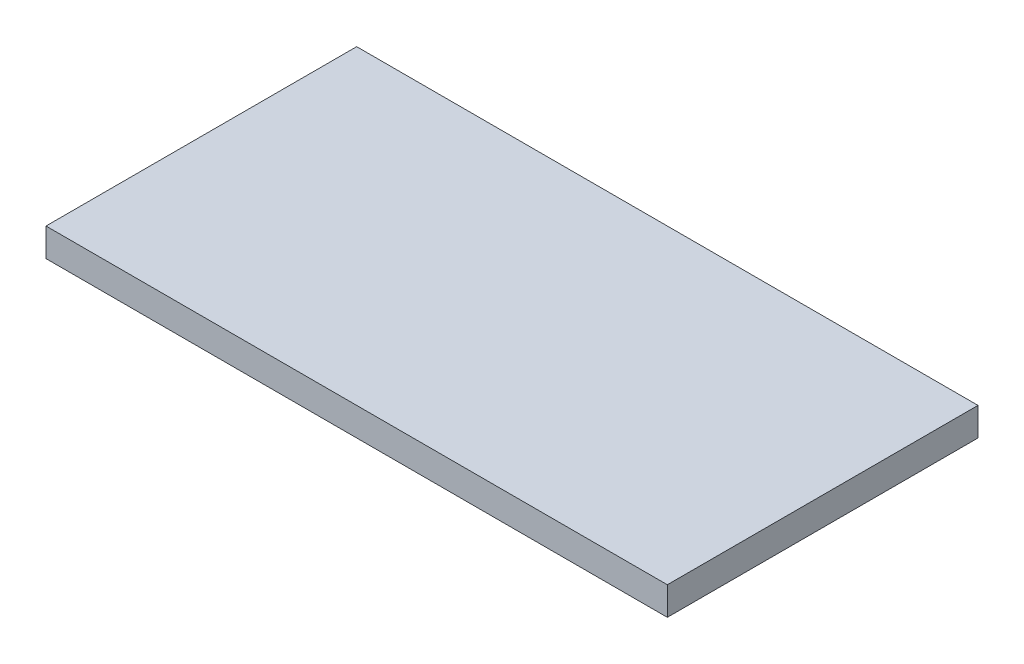
SolidWorks part; units mm, degrees
ref_plane "Front Plane" through (0, 0, 0) normal (0, 0, 1) x (1, 0, 0)
ref_plane "Top Plane" through (0, 0, 0) normal (0, 1, 0) x (1, 0, 0)
ref_plane "Right Plane" through (0, 0, 0) normal (1, 0, 0) x (0, 0, -1)
sketch "Sketch1" plane through (0, 0, 0) normal (0, 1, 0) x (1, 0, 0)
  line L1 (0, 0) -> (22, 0)
  line L2 (0, 0) -> (0, -11)
  line L3 (0, -11) -> (22, -11)
  line L4 (22, 0) -> (22, -11)
  dimension "D1" = 11
  dimension "D2" = 22
extrude "Boss-Extrude1" add sketch "Sketch1" along normal blind 1
ref_plane "Plane1" through (0, 0, 5.5) normal (0, 0, 1) x (1, 0, 0)
